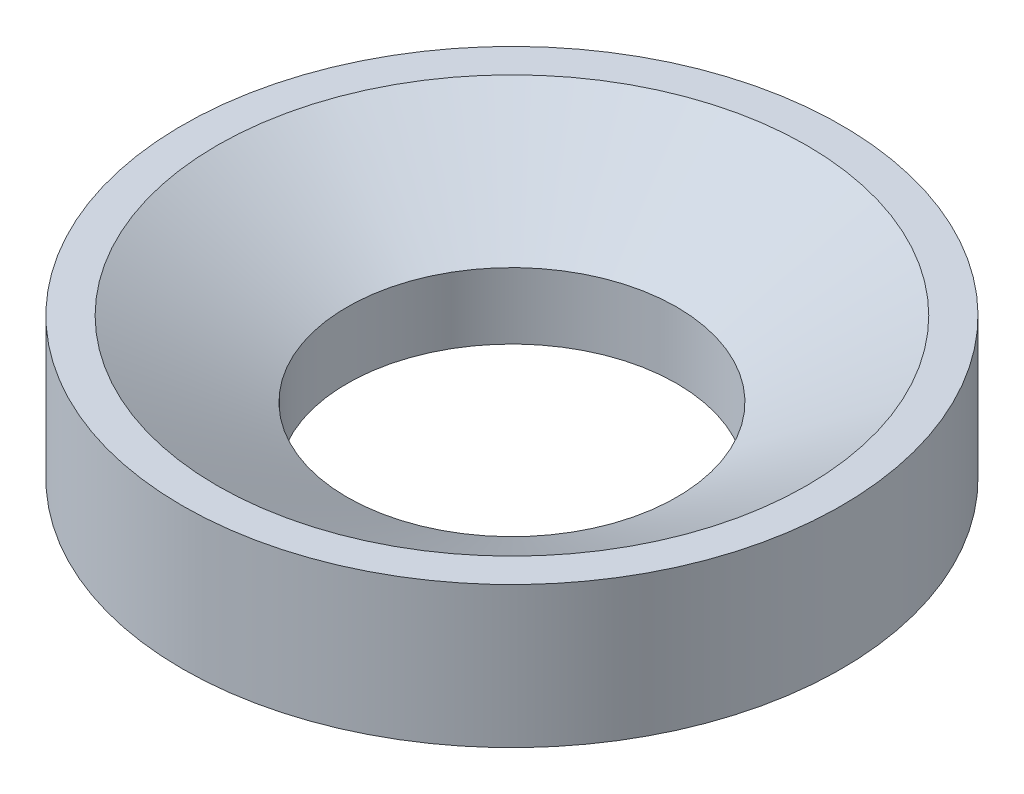
SolidWorks part; units mm, degrees
ref_plane "Front Plane" through (0, 0, 0) normal (0, 0, 1) x (1, 0, 0)
ref_plane "Top Plane" through (0, 0, 0) normal (0, 1, 0) x (1, 0, 0)
ref_plane "Right Plane" through (0, 0, 0) normal (1, 0, 0) x (0, 0, -1)
sketch "Sketch2" plane through (0, 0, 0) normal (0, 0, 1) x (1, 0, 0)
  line L5 (0, 44.6684) -> (0, -64.1085) construction
  line L8 (79.5076, 38.1) -> (88.9, 38.1)
  line L9 (44.45, 0) -> (88.9, 0)
  line L10 (88.9, 0) -> (88.9, 38.1)
  line L15 (44.45, 0) -> (44.45, 17.8595)
  line L16 (44.45, 17.8595) -> (79.5076, 38.1)
  line L17 (44.45, 17.8595) -> (92.1501, 17.8595) construction
  dimension "D1" = 44.45
  dimension "D2" = 44.45
  dimension "D3" = 38.1
  dimension "D4" = 30
revolve "Revolve1" add sketch "Sketch2" angle 360 about L5
sketch "Sketch4" plane through (0, 0, 0) normal (0, -1, 0) x (1, 0, 0)
  line L0 (0, 0) -> (0, -78.4993) construction
